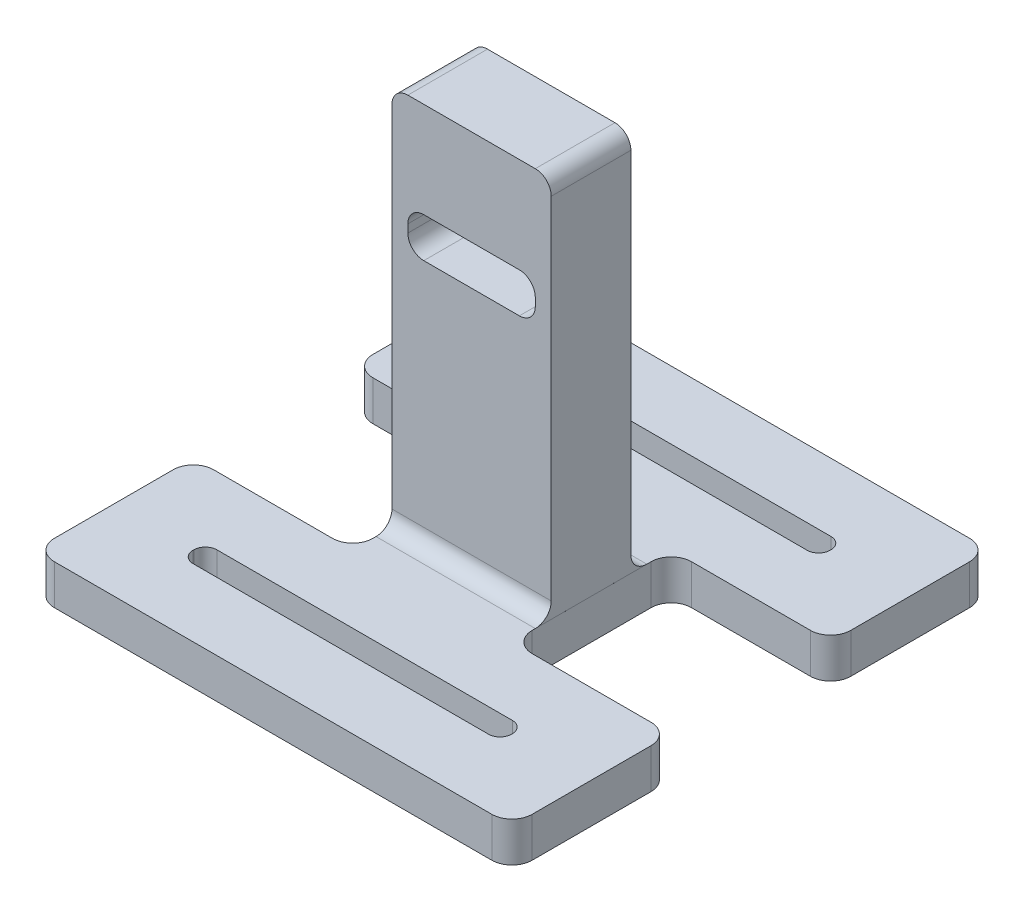
SolidWorks part; units mm, degrees
ref_plane "Front Plane" through (0, 0, 0) normal (0, 0, 1) x (1, 0, 0)
ref_plane "Top Plane" through (0, 0, 0) normal (0, 1, 0) x (1, 0, 0)
ref_plane "Right Plane" through (0, 0, 0) normal (1, 0, 0) x (0, 0, -1)
sketch "Sketch1" plane through (0, 0, 0) normal (0, 1, 0) x (1, 0, 0)
  line L0 (0.0004, -29.9264) -> (0.0004, 30.0736) construction
  line L1 (-29.9996, -29.9264) -> (30.0004, -29.9264)
  line L2 (-29.9996, -29.9264) -> (-29.9996, -9.9264)
  line L3 (-29.9996, 30.0736) -> (30.0004, 30.0736)
  line L4 (30.0004, -29.9264) -> (30.0004, -9.9264)
  line L5 (10.0004, -9.9264) -> (30.0004, -9.9264)
  line L6 (-9.9996, -9.9264) -> (-29.9996, -9.9264)
  line L7 (10.0004, 10.0736) -> (-9.9996, 10.0736) construction
  line L8 (10.0004, 10.0736) -> (10.0004, -9.9264)
  line L9 (10.0004, -9.9264) -> (-9.9996, -9.9264) construction
  line L10 (-9.9996, 10.0736) -> (-9.9996, -9.9264)
  line L11 (-29.9996, 30.0736) -> (-29.9996, 10.0736)
  line L12 (30.0004, 30.0736) -> (30.0004, 10.0736)
  line L13 (10.0004, 10.0736) -> (-9.9996, -9.9264) construction
  line L14 (10.0004, -9.9264) -> (-9.9996, 10.0736) construction
  line L15 (30.0004, 10.0736) -> (10.0004, 10.0736)
  line L16 (-9.9996, 10.0736) -> (-29.9996, 10.0736)
  point P9 (0.0004, 0.0736)
  dimension "D1" = 60
  dimension "D2" = 60
  dimension "D3" = 20
  dimension "D5" = 20
  dimension "D6" = 20
extrude "Boss-Extrude1" add sketch "Sketch1" along normal blind 5
sketch "Sketch2" plane through (0, 5, 0) normal (0, 1, 0) x (1, 0, 0)
  line L0 (-29.9996, 20.0736) -> (30.0004, 20.0736) construction
  line L1 (-29.9996, 30.0736) -> (-29.9996, 10.0736) construction
  line L2 (30.0004, 30.0736) -> (30.0004, 10.0736) construction
  line L8 (-29.9996, -19.9264) -> (30.0004, -19.9264) construction
  line L9 (-29.9996, -29.9264) -> (-29.9996, -9.9264) construction
  line L10 (30.0004, -29.9264) -> (30.0004, -9.9264) construction
  line L17 (-18.5492, 18.5736) -> (18.55, 18.5736)
  line L18 (-19.9992, 20.0236) -> (-19.9992, 20.1236)
  line L19 (-18.5492, 21.5736) -> (18.55, 21.5736)
  line L20 (20, 20.0236) -> (20, 20.1236)
  line L21 (-19.9992, 18.5736) -> (20, 21.5736) construction
  line L22 (-19.9992, 21.5736) -> (20, 18.5736) construction
  line L23 (-18.5496, -21.4264) -> (18.5504, -21.4264)
  line L24 (-19.9996, -19.9764) -> (-19.9996, -19.8764)
  line L25 (-18.5496, -18.4264) -> (18.5504, -18.4264)
  line L26 (20.0004, -19.9764) -> (20.0004, -19.8764)
  line L27 (-19.9996, -21.4264) -> (20.0004, -18.4264) construction
  line L28 (-19.9996, -18.4264) -> (20.0004, -21.4264) construction
  arc A0 (-18.5496, -21.4264) -> (-19.9996, -19.9764) centre (-18.5496, -19.9764) cw
  arc A1 (-19.9996, -19.8764) -> (-18.5496, -18.4264) centre (-18.5496, -19.8764) cw
  arc A2 (18.5504, -21.4264) -> (20.0004, -19.9764) centre (18.5504, -19.9764) ccw
  arc A3 (18.5504, -18.4264) -> (20.0004, -19.8764) centre (18.5504, -19.8764) cw
  arc A4 (18.55, 18.5736) -> (20, 20.0236) centre (18.55, 20.0236) ccw
  arc A5 (-18.5492, 18.5736) -> (-19.9992, 20.0236) centre (-18.5492, 20.0236) cw
  arc A6 (18.55, 21.5736) -> (20, 20.1236) centre (18.55, 20.1236) cw
  arc A7 (-19.9992, 20.1236) -> (-18.5492, 21.5736) centre (-18.5492, 20.1236) cw
  point P32 (0.0004, 20.0736)
  point P37 (0.0004, -19.9264)
  dimension "D3" = 1.45
  dimension "D1" = 3
  dimension "D2" = 3
  dimension "D4" = 10
extrude "Cut-Extrude1" cut sketch "Sketch2" against normal through all
fillet "Fillet1" radius 2.54 12 edges at (-29.9996, 2.5, -30.0736) (-29.9996, 2.5, 29.9264) (30.0004, 2.5, 29.9264) (30.0004, 2.5, -30.0736) (10.0004, 2.5, -10.0736) (30.0004, 2.5, -10.0736) (-29.9996, 2.5, -10.0736) (-9.9996, 2.5, -10.0736) (-29.9996, 2.5, 9.9264) (-9.9996, 2.5, 9.9264) (10.0004, 2.5, 9.9264) (30.0004, 2.5, 9.9264)
sketch "Sketch3" plane through (0, 5, 0) normal (0, 1, 0) x (1, 0, 0)
  line L1 (-10, 5) -> (10, 5)
  line L2 (-10, 5) -> (-10, -5)
  line L3 (-10, -5) -> (10, -5)
  line L4 (10, 5) -> (10, -5)
  line L5 (-10, 5) -> (10, -5) construction
  line L6 (-10, -5) -> (10, 5) construction
  point P0 (0, 0)
  dimension "D1" = 10
  dimension "D2" = 20
extrude "Boss-Extrude2" add sketch "Sketch3" along normal blind 48
sketch "Sketch4" plane through (0, 0, -5) normal (0, 0, -1) x (-1, 0, 0)
  line L0 (-10, 41) -> (10, 41) construction
  line L1 (-10, 53) -> (-10, 5) construction
  line L2 (10, 53) -> (10, 5) construction
  line L3 (-10, 53) -> (10, 53) construction
  line L5 (8, 41) -> (-8, 41)
  line L6 (8, 41) -> (8, 36)
  line L7 (8, 36) -> (-8, 36)
  line L8 (-8, 41) -> (-8, 36)
  point P8 (8, 41)
  point P9 (0, 41)
  dimension "D1" = 12
  dimension "D2" = 8
  dimension "D3" = 16
  dimension "D4" = 5
extrude "Cut-Extrude4" cut sketch "Sketch4" against normal blind 32
fillet "Fillet2" radius 2 8 edges at (-8, 41, 0) (8, 36, 0) (-8, 36, 0) (8, 41, 0) (0.0002, 5, -5) (0.0002, 5, 5) (-10, 53, 0) (10, 53, 0)
